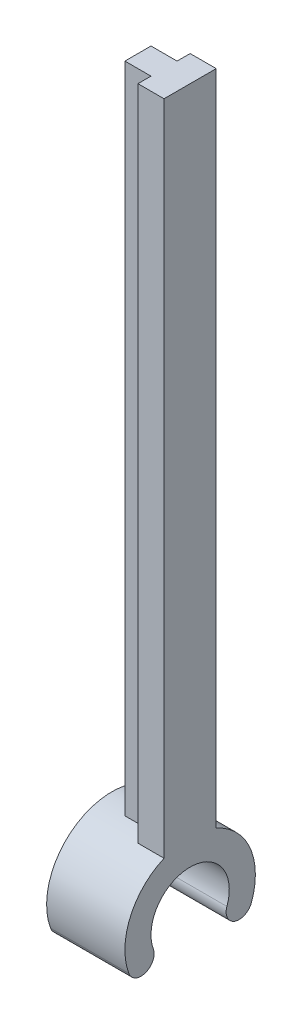
SolidWorks part; units mm, degrees
ref_plane "Front" through (0, 0, 0) normal (0, 0, 1) x (1, 0, 0)
ref_plane "Top" through (0, 0, 0) normal (0, 1, 0) x (1, 0, 0)
ref_plane "Right" through (0, 0, 0) normal (1, 0, 0) x (0, 0, -1)
sketch "Sketch1" plane through (0, 0, 0) normal (1, 0, 0) x (0, 0, -1)
  line L0 (0, 0) -> (-5, 0)
  line L1 (0, 0) -> (-4.6985, -1.7101)
  line L2 (0, 50) -> (0, -50) construction
  line L3 (0, 0) -> (4.6985, -1.7101)
  line L4 (-4.6985, -1.7101) -> (-3.7588, -1.3681)
  circle A0 centre (0, 0) radius 3
  circle A1 centre (0, 0) radius 5
  arc A2 (-4.6985, -1.7101) -> (-2.8191, -1.0261) centre (-3.7588, -1.3681) ccw
  arc A3 (4.6985, -1.7101) -> (2.8191, -1.0261) centre (3.7588, -1.3681) cw
  dimension "D1" = 20
  dimension "D3" = 10
  dimension "D4" = 6
  dimension "D2" = 1
extrude "Boss-Extrude1" add sketch "Sketch1" against normal blind 4 and the other way blind 2 contours L3 A1 L0 A0 | A3 L3 | L0 A1 L1 A0 | L1 A2
sketch "Sketch2" plane through (0, 0, 0) normal (1, 0, 0) x (0, 0, -1)
  line L0 (0, 0) -> (0, 5)
  line L1 (0, 5) -> (0, 3)
  line L2 (0, 3) -> (-2, 3)
  line L4 (-2, 3) -> (2, 3)
  line L5 (-2, 3) -> (-2, 55)
  line L6 (-2, 55) -> (2, 55)
  line L7 (2, 3) -> (2, 55)
  arc A0 (4.6985, -1.7101) -> (-4.6985, -1.7101) centre (0, 0) ccw construction
  dimension "D1" = 2
  dimension "D2" = 2
  dimension "D3" = 4
  dimension "D4" = 52
extrude "Boss-Extrude2" add sketch "Sketch2" along normal blind 2
sketch "Sketch3" plane through (0, 0, 0) normal (1, 0, 0) x (0, 0, -1)
  line L0 (0, 55) -> (-1, 55)
  line L1 (-2, 55) -> (2, 55) construction
  line L3 (-1, 55) -> (1, 55)
  line L4 (-1, 55) -> (-1, 3)
  line L5 (-1, 3) -> (1, 3)
  line L6 (1, 55) -> (1, 3)
  dimension "D1" = 1
  dimension "D2" = 52
  dimension "D3" = 2
extrude "Boss-Extrude3" add sketch "Sketch3" against normal blind 2 contours L6 L3 L0 L4 L5
